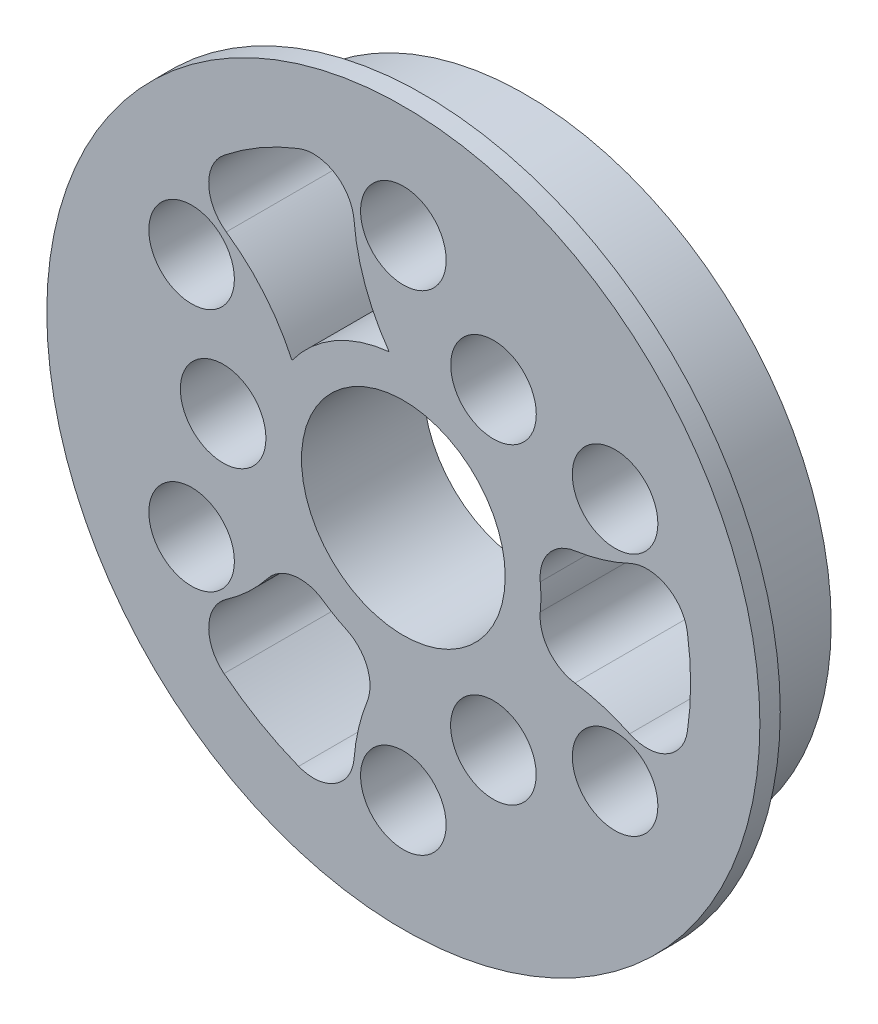
SolidWorks part; units mm, degrees
material "6061 合金"
ref_plane "前视基准面" through (0, 0, 0) normal (0, 0, 1) x (1, 0, 0)
ref_plane "上视基准面" through (0, 0, 0) normal (0, 1, 0) x (1, 0, 0)
ref_plane "右视基准面" through (0, 0, 0) normal (1, 0, 0) x (0, 0, -1)
other "Configuration Table"
sketch "草图1" plane through (0, 0, 0) normal (0, 0, 1) x (1, 0, 0)
  line L0 (0, 0) -> (21.3337, 0) construction
  line L1 (0, 0) -> (14.317, 24.7977) construction
  circle A0 centre (0, 0) radius 15
  circle A1 centre (0, 0) radius 12 construction
  circle A2 centre (0, 12) radius 2.1
  circle A3 centre (10.3923, 6) radius 2.1
  circle A4 centre (10.3923, -6) radius 2.1
  circle A5 centre (0, -12) radius 2.1
  circle A6 centre (-10.3923, -6) radius 2.1
  circle A7 centre (-10.3923, 6) radius 2.1
  circle A8 centre (0, 0) radius 8.85 construction
  circle A9 centre (4.425, 7.6643) radius 2.1
  circle A10 centre (4.4197, -7.6551) radius 2.1
  circle A11 centre (-8.8447, 0.0092) radius 2.1
  point P18 (0, 0)
  point P29 (0, 0.0061)
  dimension "D1" = 30
  dimension "D2" = 24
  dimension "D3" = 6
  dimension "D4" = 17.7
  dimension "D6" = 3
  dimension "D7" = 8.85
  dimension "D8" = 4.2
  dimension "D9" = 4.2
  dimension "D5" = 60
extrude "凸台-拉伸1" add sketch "草图1" along normal blind 6
sketch "草图2" plane through (0, 0, 6) normal (0, 0, 1) x (1, 0, 0)
  circle A0 centre (-8.8447, 0.0092) radius 2.1 construction
  circle A2 centre (0, 0) radius 17.5
  circle A3 centre (-10.3923, -6) radius 2.1 construction
  circle A4 centre (0, -12) radius 2.1 construction
  circle A5 centre (4.4197, -7.6551) radius 2.1 construction
  circle A6 centre (10.3923, -6) radius 2.1 construction
  circle A7 centre (-8.8447, 0.0092) radius 2.1
  circle A8 centre (-10.3923, -6) radius 2.1
  circle A9 centre (0, -12) radius 2.1
  circle A10 centre (4.4197, -7.6551) radius 2.1
  circle A11 centre (10.3923, -6) radius 2.1
  circle A12 centre (10.3923, 6) radius 2.1 construction
  circle A13 centre (4.425, 7.6643) radius 2.1 construction
  circle A14 centre (0, 12) radius 2.1 construction
  circle A15 centre (-10.3923, 6) radius 2.1 construction
  circle A16 centre (10.3923, 6) radius 2.1
  circle A17 centre (4.425, 7.6643) radius 2.1
  circle A18 centre (0, 12) radius 2.1
  circle A19 centre (-10.3923, 6) radius 2.1
  dimension "D1" = 35
extrude "凸台-拉伸2" add sketch "草图2" against normal blind 1
sketch "草图3" plane through (0, 0, 6) normal (0, 0, 1) x (1, 0, 0)
  circle A0 centre (0, 0) radius 5
  dimension "D1" = 10
extrude "切除-拉伸1" cut sketch "草图3" against normal blind 10
sketch "草图4" plane through (0, 0, 0) normal (0, 0, -1) x (-1, 0, 0)
  line L0 (0, 0) -> (-4.425, 7.6643) construction
  line L1 (-4.425, 7.6643) -> (-7.05, 12.211) construction
  line L2 (0, 0) -> (49999.973, 51.9548) construction
  line L3 (0, 0) -> (-25000, -43301.2702) construction
  circle A0 centre (0, 0) radius 14.1
  circle A1 centre (0, 0) radius 6.75
  circle A2 centre (-7.05, 12.211) radius 9.5
  circle A3 centre (14.1, 0) radius 9.5
  circle A4 centre (-7.05, -12.211) radius 9.5
  dimension "D1" = 19
  dimension "D2" = 19
  dimension "D3" = 19
extrude "切除-拉伸3" cut sketch "草图4" against normal blind 10 contours A4 A1 A2 A0 | A3 A0 A2 A1 | A4 A0 A3 A1
fillet "圆角1" radius 2 10 edges at (-2.2965, -13.9117, 3) (13.1962, -4.967, 3) (-0.698, -6.7138, 3) (6.1633, -2.7524, 3) (6.1633, 2.7524, 3) (-2.2965, 13.9117, 3) (13.1962, 4.967, 3) (-10.8996, 8.9447, 3) (-10.8996, -8.9447, 3) (-5.4653, -3.9614, 3)
